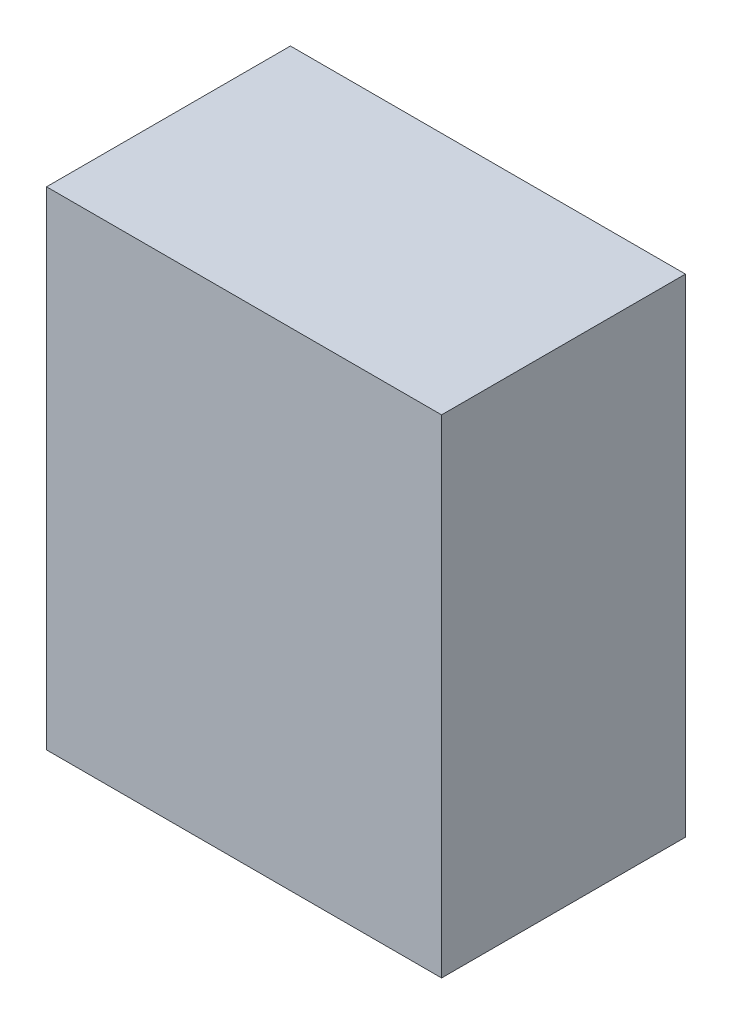
SolidWorks part; units mm, degrees
ref_plane "Front Plane" through (0, 0, 0) normal (0, 0, 1) x (1, 0, 0)
ref_plane "Top Plane" through (0, 0, 0) normal (0, 1, 0) x (1, 0, 0)
ref_plane "Right Plane" through (0, 0, 0) normal (1, 0, 0) x (0, 0, -1)
sketch "Sketch1" plane through (0, 0, 0) normal (0, 0, 1) x (1, 0, 0)
  line L1 (0, 0) -> (16.2, 0)
  line L2 (0, 0) -> (0, 20)
  line L3 (0, 20) -> (16.2, 20)
  line L4 (16.2, 0) -> (16.2, 20)
extrude "Boss-Extrude1" add sketch "Sketch1" against normal blind 10
